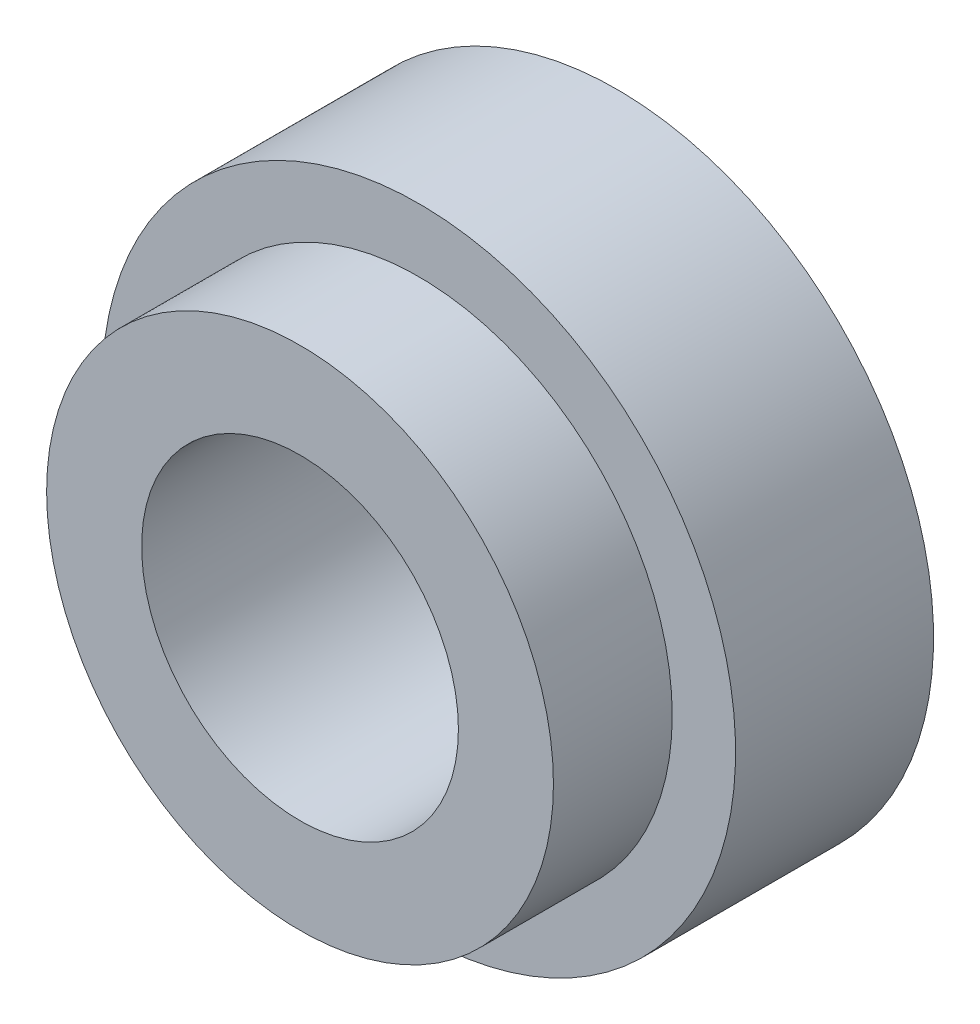
SolidWorks part; units mm, degrees
ref_plane "Front Plane" through (0, 0, 0) normal (0, 0, 1) x (1, 0, 0)
ref_plane "Top Plane" through (0, 0, 0) normal (0, 1, 0) x (1, 0, 0)
ref_plane "Right Plane" through (0, 0, 0) normal (1, 0, 0) x (0, 0, -1)
sketch "Sketch1" plane through (0, 0, 0) normal (0, 0, 1) x (1, 0, 0)
  circle A2 centre (0, -22) radius 6.4
  circle A3 centre (0, -22) radius 6.4
  dimension "D1" = 0.1
extrude "Extrude1" add sketch "Sketch1" against normal up to surface (3 mm away)
sketch "Sketch2" plane through (0, 0, -3) normal (0, 0, -1) x (-1, 0, 0)
  circle A0 centre (0, -22) radius 8
  dimension "D1" = 16
extrude "Extrude2" add sketch "Sketch2" along normal blind 5
sketch "Sketch3" plane through (0, 0, 0) normal (0, 0, 1) x (1, 0, 0)
  circle A0 centre (0, -22) radius 4
  circle A1 centre (0, -22) radius 6.4 construction
  dimension "D1" = 8
extrude "Cut-Extrude1" cut sketch "Sketch3" against normal through all
